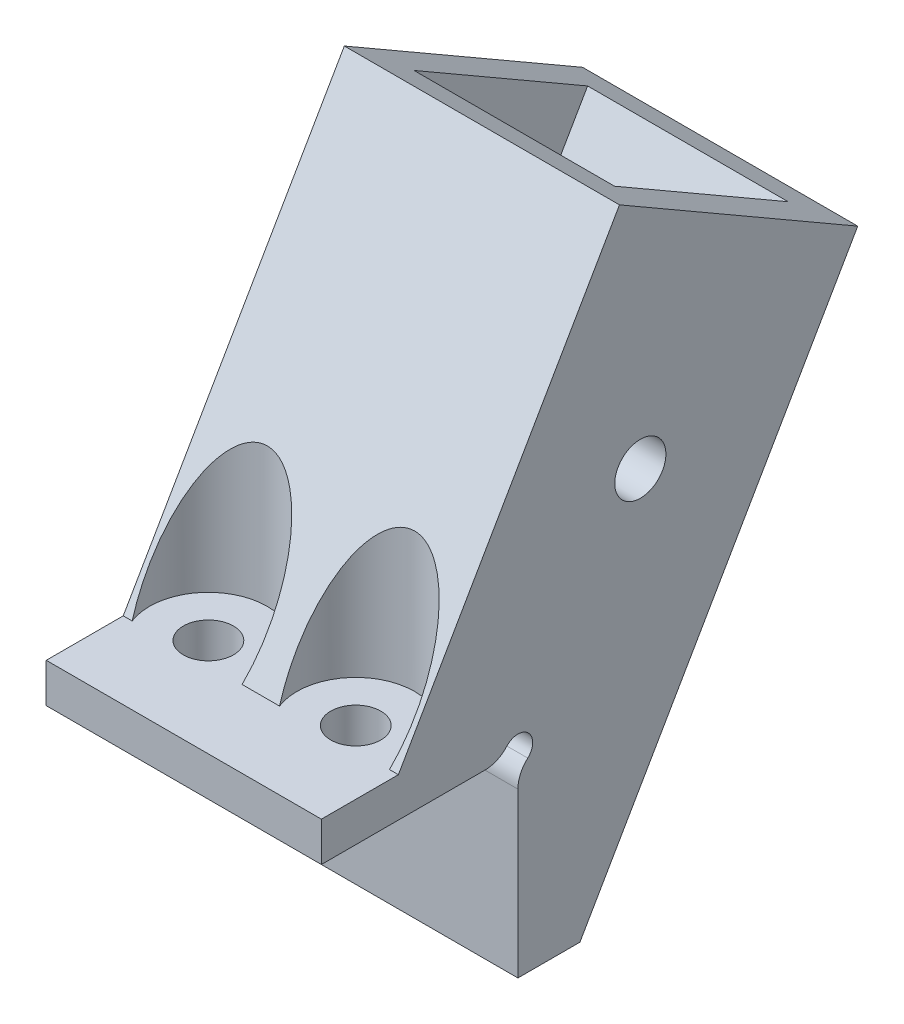
SolidWorks part; units mm, degrees
material "PA Type 6"
ref_plane "Front Plane" through (0, 0, 0) normal (0, 0, 1) x (1, 0, 0)
ref_plane "Top Plane" through (0, 0, 0) normal (0, 1, 0) x (1, 0, 0)
ref_plane "Right Plane" through (0, 0, 0) normal (1, 0, 0) x (0, 0, -1)
sketch "Sketch1" plane through (0, 0, 0) normal (1, 0, 0) x (0, 0, -1)
  line L0 (0, 0) -> (-24, 0)
  line L1 (-24, 0) -> (-24, -4)
  line L2 (-24, -4) -> (-4, -4)
  line L3 (-4, -4) -> (-4, -24)
  line L4 (-4, -24) -> (0, -24)
  line L5 (0, -24) -> (0, 0)
  dimension "D1" = 24
  dimension "D2" = 24
  dimension "D3" = 20
  dimension "D4" = 20
extrude "Boss-Extrude1" add sketch "Sketch1" along normal blind 28
sketch "Sketch2" plane through (28, 0, 0) normal (1, 0, 0) x (0, 0, -1)
  line L0 (0, 0) -> (20.2636, 35.0976) construction
  line L1 (0, 0) -> (19.1631, 0) construction
  line L2 (2.3094, -24) -> (30.5829, 24.9711)
  line L3 (-16.1658, 0) -> (6.3342, 38.9711)
  line L4 (0, -24) -> (2.3094, -24)
  line L5 (0, 0) -> (-24, 0) construction
  line L8 (0, -24) -> (0, 0)
  line L9 (0, 0) -> (-16.1658, 0)
  line L11 (6.3342, 38.9711) -> (30.5829, 24.9711)
  dimension "D1" = 60
  dimension "D4" = 45
  dimension "D2" = 14
  dimension "D3" = 14
extrude "Boss-Extrude2" add sketch "Sketch2" against normal blind 28
sketch "Sketch3" plane through (0, -4, 0) normal (0, -1, 0) x (1, 0, 0)
  line L0 (0, 14) -> (28, 14) construction
  line L1 (0, 24) -> (0, 4) construction
  line L2 (28, 24) -> (28, 4) construction
  line L3 (14, 24) -> (14, 4) construction
  line L4 (28, 24) -> (0, 24) construction
  line L5 (28, 4) -> (0, 4) construction
  circle A1 centre (6.5, 14) radius 2.55
  circle A2 centre (21.5, 14) radius 2.55
  dimension "D1" = 5.1
  dimension "D2" = 7.5
extrude "Cut-Extrude1" cut sketch "Sketch3" against normal through all
sketch "Sketch4" plane through (0, 0, 0) normal (0, 1, 0) x (1, 0, 0)
  circle A0 centre (6.5, -14) radius 6
  circle A1 centre (21.5, -14) radius 6
  dimension "D1" = 12
  dimension "D2" = 12
extrude "Cut-Extrude2" cut sketch "Sketch4" along normal blind 28
sketch "Sketch5" plane through (0, 31.9711, -18.4585) normal (0, 0.866, -0.5) x (1, 0, 0)
  line L0 (3.8, 10.2) -> (24.2, 10.2)
  line L1 (24.2, 10.2) -> (24.2, -10.2)
  line L2 (24.2, -10.2) -> (3.8, -10.2)
  line L3 (3.8, 10.2) -> (3.8, -10.2)
  line L4 (0, 14) -> (28, 14) construction
  line L5 (28, 14) -> (28, -14) construction
  line L6 (0, -14) -> (28, -14) construction
  line L7 (0, 14) -> (0, -14) construction
  dimension "D1" = 3.8
  dimension "D2" = 3.8
  dimension "D3" = 3.8
  dimension "D4" = 3.8
extrude "Cut-Extrude3" cut sketch "Sketch5" against normal blind 30
sketch "Sketch6" plane through (3.8, 0, 0) normal (1, 0, 0) x (0, 0, -1)
  line L0 (12.292, 0.8904) -> (3.4585, 5.9904)
  line L1 (12.292, 0.8904) -> (-5.3749, 11.0904) construction
  line L2 (3.4585, 5.9904) -> (3.4585, -14.4096)
  line L3 (3.4585, -14.4096) -> (12.292, 0.8904)
extrude "Cut-Extrude4" cut sketch "Sketch6" along normal blind 20.4
sketch "Sketch7" plane through (28, 0, 0) normal (1, 0, 0) x (0, 0, -1)
  line L0 (0, 0) -> (16.1784, 28.0218) construction
  line L1 (0, 0) -> (28.3839, 0) construction
  line L2 (30.5829, 24.9711) -> (6.3342, 38.9711) construction
  circle A0 centre (8.4585, 14.6506) radius 2.6
  dimension "D2" = 5.2
  dimension "D1" = 60
  dimension "D3" = 20
extrude "Cut-Extrude5" cut sketch "Sketch7" against normal through all
sketch "Sketch8" plane through (28, 0, 0) normal (1, 0, 0) x (0, 0, -1)
  circle A0 centre (-4, -4) radius 1.5
  dimension "D1" = 3
extrude "Cut-Extrude6" cut sketch "Sketch8" against normal through all
fillet "Fillet2" radius 3 2 edges at (14, -5.5, 4) (14, -4, 5.5)
